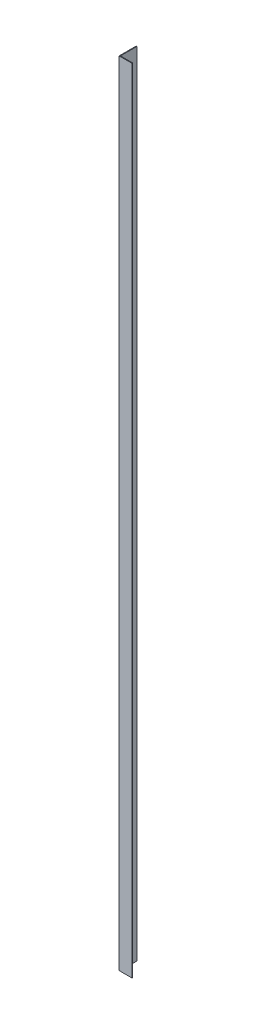
SolidWorks part; units mm, degrees
ref_plane "Front Plane" through (0, 0, 0) normal (0, 0, 1) x (1, 0, 0)
ref_plane "Top Plane" through (0, 0, 0) normal (0, 1, 0) x (1, 0, 0)
ref_plane "Right Plane" through (0, 0, 0) normal (1, 0, 0) x (0, 0, -1)
other "Configuration Table"
sketch "Sketch1" plane through (0, 0, 0) normal (0, 1, 0) x (1, 0, 0)
  line L0 (700, -40) -> (700, -38.5)
  line L1 (700, -38.5) -> (671.5, -38.5)
  line L2 (671.5, -38.5) -> (671.5, 0)
  line L3 (671.5, 0) -> (670, 0)
  line L4 (670, 0) -> (670, -40)
  line L5 (670, -40) -> (700, -40)
extrude "PRESS_sove_sag_1" add sketch "Sketch1" along normal blind 1850 from offset 120 separate body
